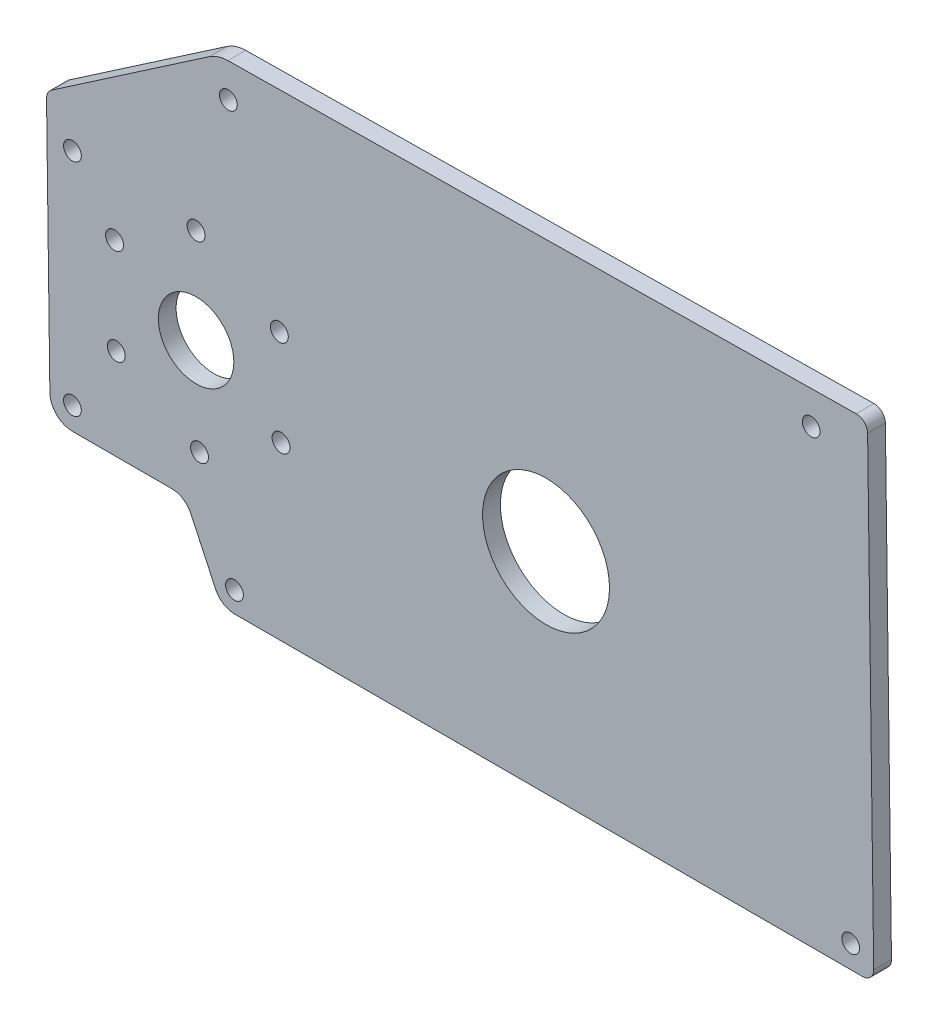
SolidWorks part; units mm, degrees
ref_plane "Front Plane" through (0, 0, 0) normal (0, 0, 1) x (1, 0, 0)
ref_plane "Top Plane" through (0, 0, 0) normal (0, 1, 0) x (1, 0, 0)
ref_plane "Right Plane" through (0, 0, 0) normal (1, 0, 0) x (0, 0, -1)
sketch "Sketch1" plane through (0, 0, 0) normal (0, 0, 1) x (1, 0, 0)
  line L15 (16.7683, 33.6255) -> (39.2181, 33.6255) construction
  line L35 (17.5661, -48.5742) -> (-4.8581, -48.5742)
  line L73 (21.8007, -51.2691) -> (27.3987, -63.2442)
  line L74 (31.6333, -65.9391) -> (66.5236, -65.9391)
  line L77 (66.5236, -65.9391) -> (173.0612, -65.9391)
  line L81 (-4.8581, -43.4942) -> (-4.8581, 16.476) construction
  line L84 (30.1658, 41.2448) -> (171.6576, 43.1095)
  line L86 (174.2308, 40.6031) -> (175.601, -63.3656)
  line L88 (39.2181, 33.6255) -> (62.4224, 33.6255) construction
  line L89 (16.7683, 33.6255) -> (25.9645, 39.9151)
  line L90 (-6.6198, 17.6295) -> (-9.583, 15.6029)
  line L91 (-10.6888, 13.4729) -> (-9.9381, -43.4942)
  line L92 (-6.6198, 17.6295) -> (16.7683, 33.6255)
  circle A32 centre (-4.8581, -43.4942) radius 2
  circle A46 centre (101.8113, -18.6491) radius 14.29
  circle A47 centre (31.6333, -61.2647) radius 2
  circle A52 centre (30.2662, 33.6255) radius 2
  arc A57 (31.6333, -65.9391) -> (27.3987, -63.2442) centre (31.6333, -61.2647) cw
  arc A58 (21.8007, -51.2691) -> (17.5661, -48.5742) centre (17.5661, -53.2487) ccw
  circle A59 centre (170.4264, -60.7758) radius 2
  circle A60 centre (161.5139, 35.5525) radius 2
  arc A66 (173.0612, -65.9391) -> (175.601, -63.3656) centre (173.0612, -63.3991) ccw
  arc A67 (174.2308, 40.6031) -> (171.6576, 43.1095) centre (171.6911, 40.5697) ccw
  arc A69 (-4.8581, -48.5742) -> (-9.9381, -43.4942) centre (-4.8581, -43.4942) cw
  circle A70 centre (-4.8581, 6.1453) radius 2
  arc A72 (30.1658, 41.2448) -> (25.9645, 39.9151) centre (30.2662, 33.6255) ccw
  circle A73 centre (5.0163, -27.9553) radius 2.0193
  circle A75 centre (4.63, -6.5309) radius 2.0193
  circle A76 centre (22.9909, 4.5157) radius 2.0193
  circle A77 centre (41.738, -5.8619) radius 2.0193
  circle A78 centre (42.1243, -27.2862) radius 2.0193
  circle A79 centre (23.7635, -38.3329) radius 2.0193
  arc A80 (-10.6888, 13.4729) -> (-9.583, 15.6029) centre (-8.1491, 13.5063) cw
  circle A81 centre (22.9909, -16.8933) radius 8.5
  point P0 (0, 0)
  point P35 (103.8286, -4.5315)
  point P54 (23.3772, -16.9086)
  point P56 (22.9909, 4.5157)
  point P57 (0, 0)
  point P58 (0, 0)
  point P59 (22.9909, -16.8933)
  dimension "D1" = 4
  dimension "D2" = 5.08
  dimension "D3" = 2.54
  dimension "D4" = 2.54
  dimension "D5" = 28.58
  dimension "D6" = 4
  dimension "D7" = 6
extrude "Boss-Extrude1" add sketch "Sketch1" along normal blind 4
